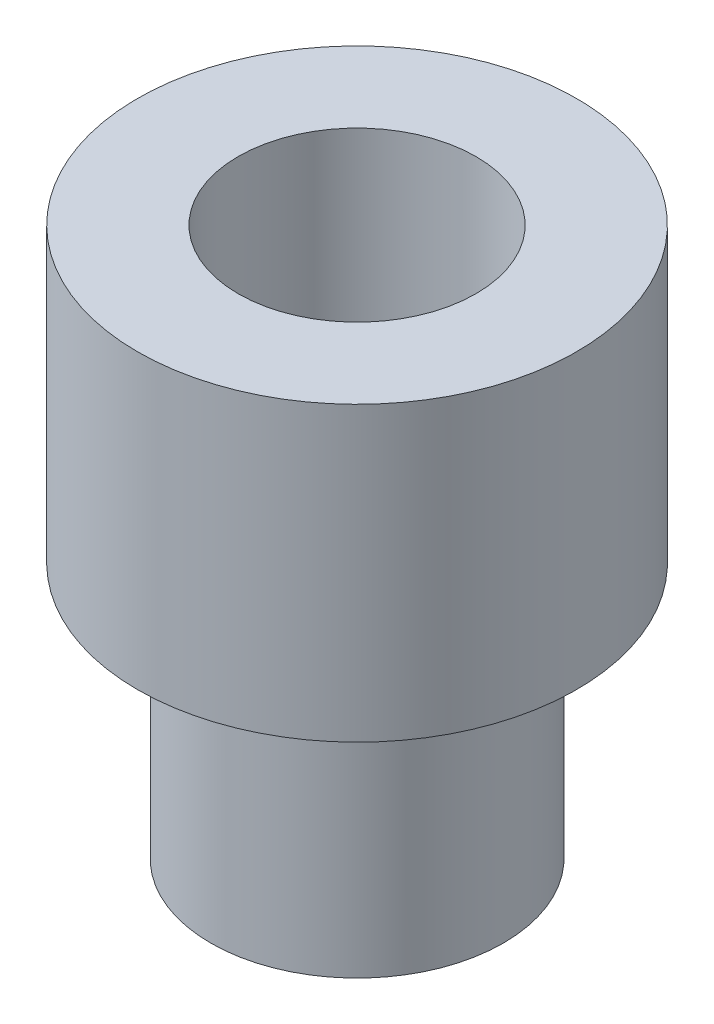
SolidWorks part; units mm, degrees
ref_plane "Alzado" through (0, 0, 0) normal (0, 0, 1) x (1, 0, 0)
ref_plane "Planta" through (0, 0, 0) normal (0, 1, 0) x (1, 0, 0)
ref_plane "Vista lateral" through (0, 0, 0) normal (1, 0, 0) x (0, 0, -1)
sketch "Croquis1" plane through (0, 0, 0) normal (0, 1, 0) x (1, 0, 0)
  circle A0 centre (0, 0) radius 3.25
  circle A1 centre (0, 0) radius 6
  dimension "D1" = 6.5
  dimension "D2" = 12
extrude "Saliente-Extruir1" add sketch "Croquis1" along normal blind 8
sketch "Croquis2" plane through (0, 0, 0) normal (0, -1, 0) x (1, 0, 0)
  circle A0 centre (0, 0) radius 4
  circle A1 centre (0, 0) radius 3.25 construction
  circle A2 centre (0, 0) radius 3.25
  dimension "D1" = 8
extrude "Saliente-Extruir2" add sketch "Croquis2" along normal blind 7
